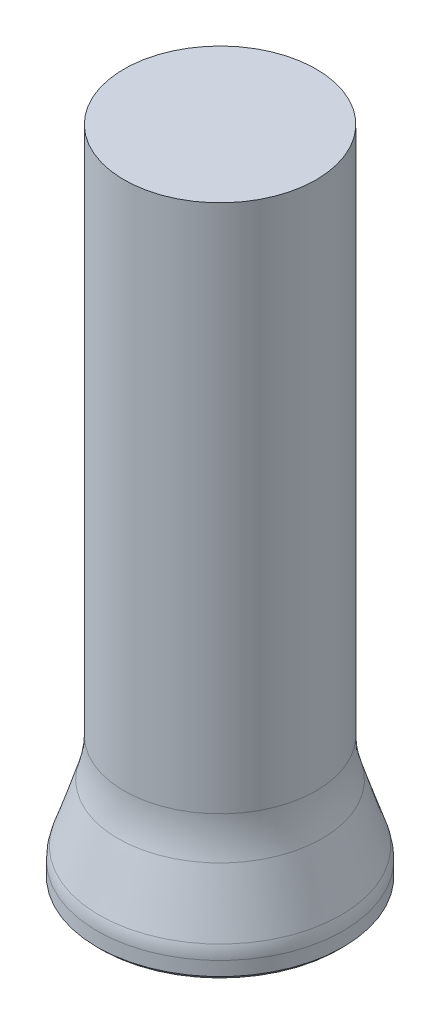
SolidWorks part; units mm, degrees
ref_plane "Płaszczyzna przednia" through (0, 0, 0) normal (0, 0, 1) x (1, 0, 0)
ref_plane "Płaszczyzna górna" through (0, 0, 0) normal (0, 1, 0) x (1, 0, 0)
ref_plane "Płaszczyzna prawa" through (0, 0, 0) normal (1, 0, 0) x (0, 0, -1)
sketch "Szkic1" plane through (0, 0, 0) normal (0, 0, 1) x (1, 0, 0)
  line L0 (0, 111.0715) -> (0, -42.9285) construction
  line L1 (0, 111.0715) -> (-23.45, 111.0715)
  line L2 (-23.45, 111.0715) -> (-23.45, -18.1411)
  line L3 (-23.45, -22.9285) -> (-23.45, -42.9285) construction
  line L4 (-24.94, -27.4782) -> (-29.5033, -41.412)
  line L5 (-23.45, -42.9285) -> (-44.2191, -42.9285) construction
  line L6 (-30, -44.5243) -> (-30, -48.9285)
  line L7 (-30, -48.9285) -> (-5, -48.9285)
  line L8 (0, -45.9285) -> (0, 111.0715)
  line L9 (0, -45.9285) -> (-5, -45.9285)
  line L10 (-5, -45.9285) -> (-5, -48.9285)
  arc A0 (-23.45, -18.1411) -> (-24.94, -27.4782) centre (-53.45, -18.1411) cw
  arc A1 (-30, -44.5243) -> (-29.5033, -41.412) centre (-20, -44.5243) cw
  point P17 (-30, -42.9285)
  dimension "D9" = 30
  dimension "D10" = 10
  dimension "D1" = 5
  dimension "D2" = 20
  dimension "D3" = 134
  dimension "D4" = 23.45
  dimension "D5" = 160
  dimension "D6" = 6
  dimension "D7" = 3
  dimension "D8" = 30
revolve "Obrót1" add sketch "Szkic1" angle 360 about L8
chamfer "Sfazowanie1" distance 1 angle 45 2 edges at (30, -48.9285, 0) (5, -48.9285, 0)
